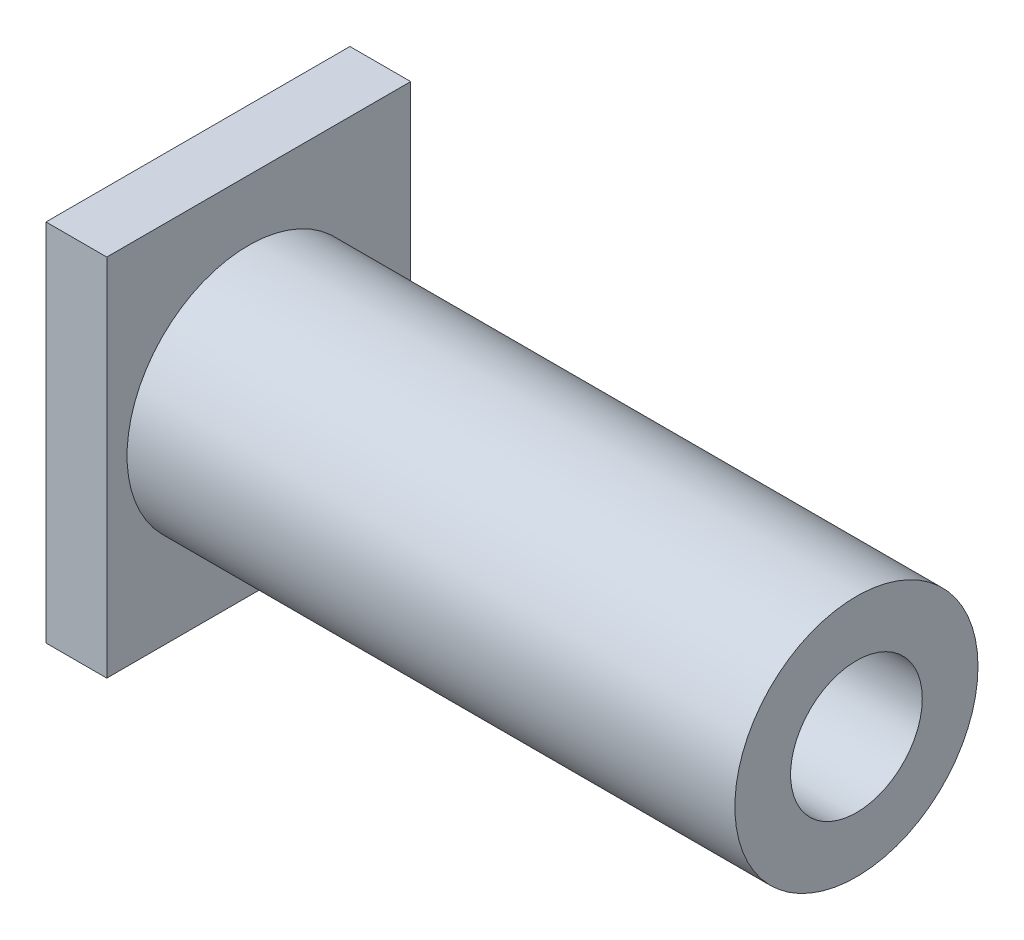
SolidWorks part; units mm, degrees
ref_plane "Front Plane" through (0, 0, 0) normal (1, 0, 0) x (0, 1, 0)
ref_plane "Top Plane" through (0, 0, 0) normal (0, 0, 1) x (0, 1, 0)
ref_plane "Right Plane" through (0, 0, 0) normal (0, 1, 0) x (-1, 0, 0)
sketch "Sketch1" plane through (0, 0, 0) normal (1, 0, 0) x (0, 1, 0)
  line L1 (-6.3372, 8.6888) -> (11.6628, 8.6888)
  line L2 (-6.3372, 8.6888) -> (-6.3372, -6.3112)
  line L3 (-6.3372, -6.3112) -> (11.6628, -6.3112)
  line L4 (11.6628, 8.6888) -> (11.6628, -6.3112)
  circle A0 centre (2.6628, 1.6888) radius 3.25
  dimension "D1" = 6.5
  dimension "D2" = 9
  dimension "D3" = 9
  dimension "D4" = 7
  dimension "D5" = 8
extrude "Boss-Extrude1" add sketch "Sketch1" along normal blind 3
sketch "Sketch2" plane through (3, 0, 0) normal (1, 0, 0) x (0, 1, 0)
  circle A0 centre (2.6628, 1.6888) radius 6
  circle A1 centre (2.6628, 1.6888) radius 3.25
  dimension "D1" = 12
extrude "Boss-Extrude2" add sketch "Sketch2" along normal blind 30
